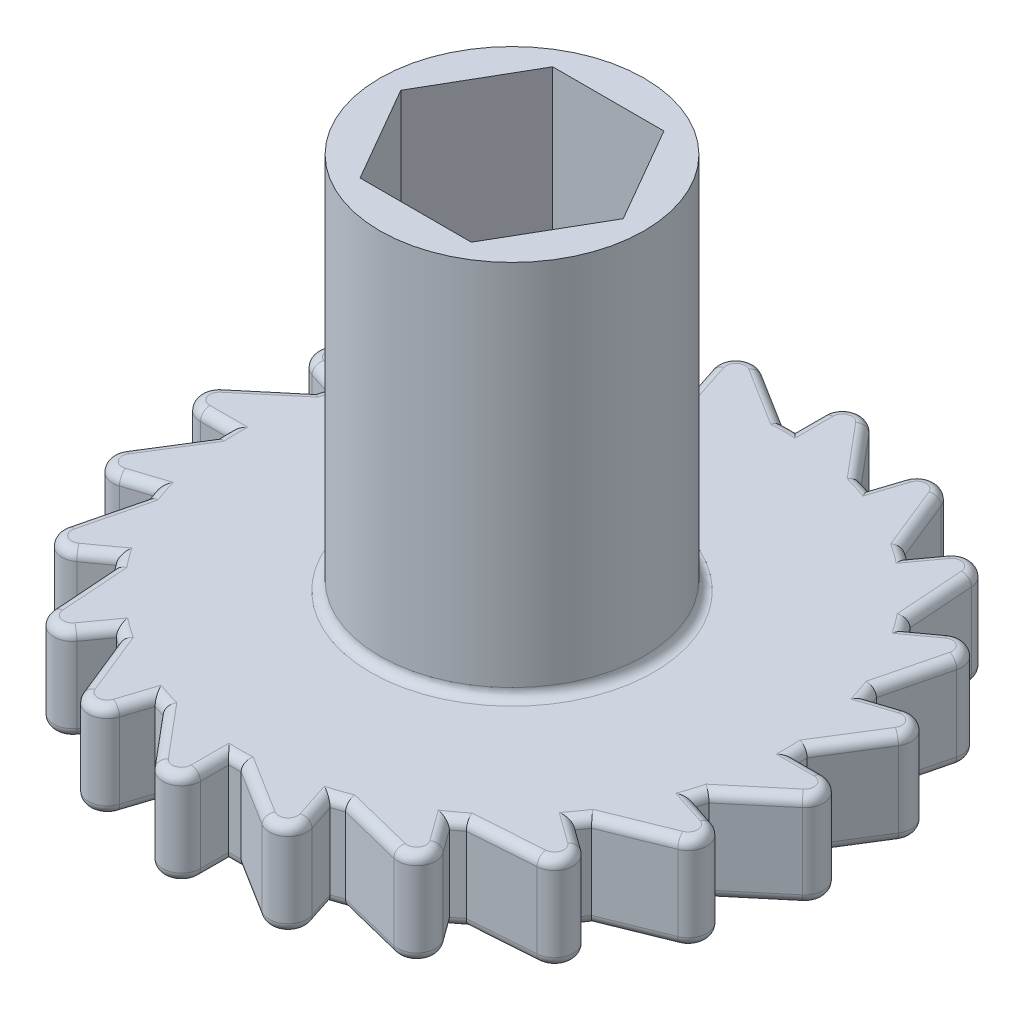
SolidWorks part; units mm, degrees
ref_plane "Front Plane" through (0, 0, 0) normal (0, 0, 1) x (1, 0, 0)
ref_plane "Top Plane" through (0, 0, 0) normal (0, 1, 0) x (1, 0, 0)
ref_plane "Right Plane" through (0, 0, 0) normal (1, 0, 0) x (0, 0, -1)
sketch "Sketch1" plane through (0, 0, 0) normal (0, 1, 0) x (1, 0, 0)
  line L1 (7.479, 0) -> (3.7395, 6.477)
  line L2 (3.7395, 6.477) -> (-3.7395, 6.477)
  line L3 (-3.7395, 6.477) -> (-7.479, 0)
  line L4 (-7.479, 0) -> (-3.7395, -6.477)
  line L5 (-3.7395, -6.477) -> (3.7395, -6.477)
  line L6 (3.7395, -6.477) -> (7.479, 0)
  circle A0 centre (0, 0) radius 6.477 construction
  circle A1 centre (0, 0) radius 19.05
  dimension "D2" = 38.1
  dimension "D1" = 12.954
extrude "Boss-Extrude1" add sketch "Sketch1" along normal blind 6.35
sketch "Sketch2" plane through (0, 6.35, 0) normal (0, 1, 0) x (1, 0, 0)
  line L1 (3.7395, 6.477) -> (-3.7395, 6.477)
  line L2 (-3.7395, 6.477) -> (-7.479, 0)
  line L3 (-7.479, 0) -> (-3.7395, -6.477)
  line L4 (-3.7395, -6.477) -> (3.7395, -6.477)
  line L5 (3.7395, -6.477) -> (7.479, 0)
  line L6 (7.479, 0) -> (3.7395, 6.477)
  circle A1 centre (0, 0) radius 6.477 construction
  circle A2 centre (0, 0) radius 8.89
  dimension "D1" = 17.78
extrude "Boss-Extrude2" add sketch "Sketch2" along normal blind 25.4
sketch "Sketch4" plane through (0, 0, 0) normal (0, -1, 0) x (1, 0, 0)
  line L1 (0, 24.4382) -> (-5.1062, 18.3529)
  line L2 (0, 24.4382) -> (9.3322, 16.6076)
  line L4 (0, 0) -> (0, 47.7347) construction
  circle A0 centre (0, 0) radius 19.05 construction
  circle A1 centre (0, 0) radius 19.05
  dimension "D1" = 40
  dimension "D2" = 50
extrude "Boss-Extrude4" add sketch "Sketch4" against normal blind 6.35
fillet "Fillet2" radius 1.27 1 edges at (0, 3.175, 24.4382)
pattern_circular "CirPattern2" count 20 over 360 about axis through (0, 0, 0) along (0, 1, 0) of "Boss-Extrude4", "Fillet2"
fillet "Fillet1" radius 0.635 167 edges at (18.388, 0, -8.8177) (18.4047, 0, -12.3389) (0, 0, -6.477) (18.388, 6.35, -8.8177) (18.4047, 6.35, -12.3389) (15.6478, 6.35, 10.865) (-5.6092, 0, -3.2385) (15.6478, 0, 10.865) (16.1799, 6.35, 11.7554) (16.1799, 0, 11.7554) (-5.6092, 0, 3.2385) (14.7632, 0, -14.0683) (13.691, 0, -17.4224) (0, 0, 6.477) (14.7632, 6.35, -14.0683) (13.691, 6.35, -17.4224) (18.2394, 6.35, 5.4977) (18.2394, 0, 5.4977) (9.6933, 0, -17.9418) (7.6371, 0, -20.8004) (19.0206, 6.35, 6.1802) (19.0206, 0, 6.1802) (9.6933, 6.35, -17.9418) (7.6371, 6.35, -20.8004) (3.6745, 0, -20.0591) (0.8356, 0, -22.1424) (19.0456, 6.35, -0.4076) (19.0456, 0, -0.4076) (3.6745, 6.35, -20.0591) (0.8356, 6.35, -22.1424) (19.9995, 6.35, 0) (19.9995, 0, 0) (-2.7039, 0, -20.2128) (-6.0476, 0, -21.3169) (-2.7039, 6.35, -20.2128) (-6.0476, 6.35, -21.3169) (17.9875, 6.35, -6.2731) (17.9875, 0, -6.2731) (19.0206, 6.35, -6.1802) (19.0206, 0, -6.1802) (-8.8177, 0, -18.388) (-12.3389, 0, -18.4047) (-8.8177, 6.35, -18.388) (-12.3389, 6.35, -18.4047) (15.1686, 6.35, -11.5245) (-14.0683, 0, -14.7632) (15.1686, 0, -11.5245) (-17.4224, 0, -13.691) (16.1799, 6.35, -11.7554) (-14.0683, 6.35, -14.7632) (-17.4224, 6.35, -13.691) (16.1799, 0, -11.7554) (-17.9418, 0, -9.6933) (-20.8004, 0, -7.6371) (-17.9418, 6.35, -9.6933) (-20.8004, 6.35, -7.6371) (10.865, 6.35, -15.6478) (10.865, 0, -15.6478) (11.7554, 6.35, -16.1799) (11.7554, 0, -16.1799) (-20.0591, 0, -3.6745) (-22.1424, 0, -0.8356) (-20.0591, 6.35, -3.6745) (-22.1424, 6.35, -0.8356) (5.4977, 6.35, -18.2394) (5.4977, 0, -18.2394) (-20.2128, 0, 2.7039) (-21.3169, 0, 6.0476) (6.1802, 6.35, -19.0206) (6.1802, 0, -19.0206) (-20.2128, 6.35, 2.7039) (-21.3169, 6.35, 6.0476) (0.4076, 0, 19.0456) (-18.388, 0, 8.8177) (-18.4047, 0, 12.3389) (-0.4076, 6.35, -19.0456) (-0.4076, 0, -19.0456) (-18.388, 6.35, 8.8177) (-18.4047, 6.35, 12.3389) (0, 6.35, -19.9995) (0, 0, -19.9995) (-14.7632, 0, 14.0683) (-13.691, 0, 17.4224) (-14.7632, 6.35, 14.0683) (-13.691, 6.35, 17.4224) (-6.2731, 6.35, -17.9875) (-6.2731, 0, -17.9875) (-6.1802, 6.35, -19.0206) (-6.1802, 0, -19.0206) (-9.6933, 0, 17.9418) (-7.6371, 0, 20.8004) (-9.6933, 6.35, 17.9418) (-7.6371, 6.35, 20.8004) (-11.5245, 6.35, -15.1686) (-11.5245, 0, -15.1686) (-11.7554, 6.35, -16.1799) (-11.7554, 0, -16.1799) (-15.6478, 6.35, -10.865) (-15.6478, 0, -10.865) (-16.1799, 6.35, -11.7554) (-16.1799, 0, -11.7554) (-18.2394, 6.35, -5.4977) (-18.2394, 0, -5.4977) (-19.0206, 6.35, -6.1802) (-19.0206, 0, -6.1802) (-19.0456, 6.35, 0.4076) (-19.0456, 0, 0.4076) (-19.9995, 6.35, 0) (-19.9995, 0, 0) (-17.9875, 6.35, 6.2731) (-17.9875, 0, 6.2731) (-19.0206, 6.35, 6.1802) (-19.0206, 0, 6.1802) (0, 6.35, 8.89) (-15.1686, 6.35, 11.5245) (-15.1686, 0, 11.5245) (-16.1799, 6.35, 11.7554) (-16.1799, 0, 11.7554) (-10.865, 6.35, 15.6478) (-10.865, 0, 15.6478) (-11.7554, 6.35, 16.1799) (-11.7554, 0, 16.1799) (-5.4977, 6.35, 18.2394) (-5.4977, 0, 18.2394) (-6.1802, 6.35, 19.0206) (-6.1802, 0, 19.0206) (2.7039, 0, 20.2128) (6.0476, 0, 21.3169) (2.7039, 6.35, 20.2128) (6.0476, 6.35, 21.3169) (0.4076, 6.35, 19.0456) (0, 6.35, 19.9995) (8.8177, 0, 18.388) (12.3389, 0, 18.4047) (0, 0, 19.9995) (8.8177, 6.35, 18.388) (12.3389, 6.35, 18.4047) (14.0683, 0, 14.7632) (17.4224, 0, 13.691) (14.0683, 6.35, 14.7632) (17.4224, 6.35, 13.691) (-3.6745, 0, 20.0591) (-0.8356, 0, 22.1424) (-3.6745, 6.35, 20.0591) (-0.8356, 6.35, 22.1424) (17.9418, 0, 9.6933) (20.8004, 0, 7.6371) (17.9418, 6.35, 9.6933) (20.8004, 6.35, 7.6371) (6.2731, 0, 17.9875) (6.2731, 6.35, 17.9875) (6.1802, 6.35, 19.0206) (6.1802, 0, 19.0206) (20.0591, 0, 3.6745) (22.1424, 0, 0.8356) (20.0591, 6.35, 3.6745) (22.1424, 6.35, 0.8356) (11.5245, 6.35, 15.1686) (20.2128, 0, -2.7039) (21.3169, 0, -6.0476) (11.5245, 0, 15.1686) (20.2128, 6.35, -2.7039) (21.3169, 6.35, -6.0476) (5.6092, 0, 3.2385) (11.7554, 6.35, 16.1799) (11.7554, 0, 16.1799) (5.6092, 0, -3.2385)
